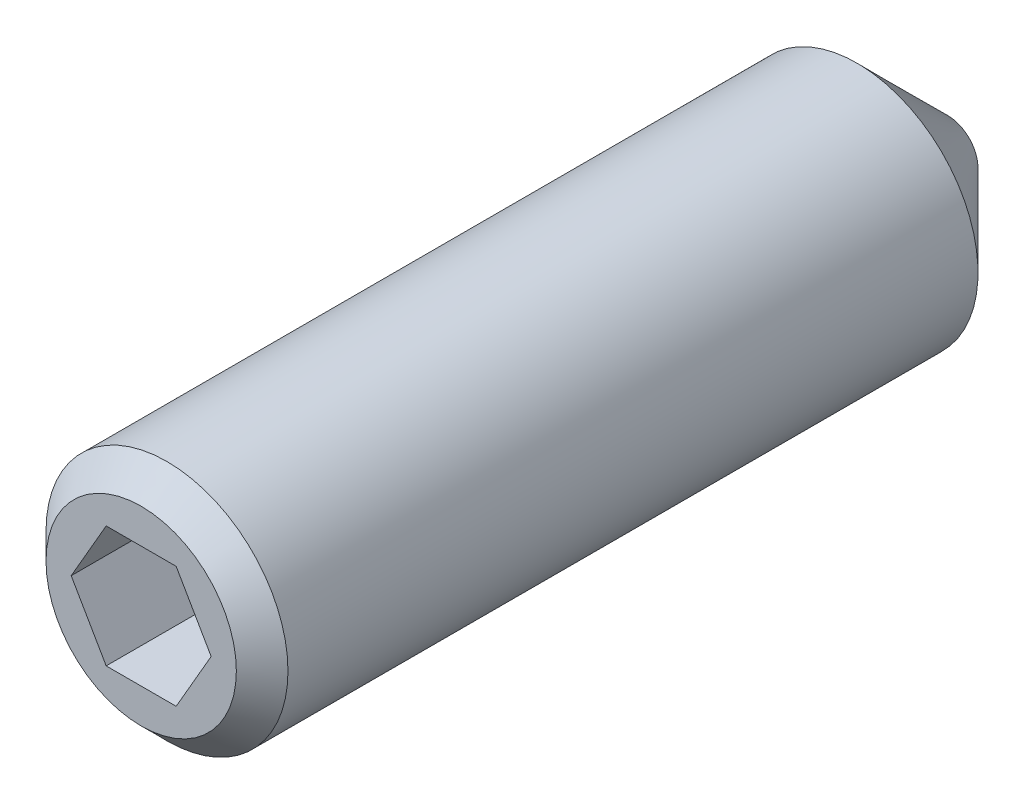
SolidWorks part; units mm, degrees
ref_plane "Front Plane" through (0, 0, 0) normal (0, 0, 1) x (1, 0, 0)
ref_plane "Top Plane" through (0, 0, 0) normal (0, 1, 0) x (1, 0, 0)
ref_plane "Right Plane" through (0, 0, 0) normal (1, 0, 0) x (0, 0, -1)
sketch "Sketch1" plane through (0, 0, 0) normal (0, 0, 1) x (1, 0, 0)
  circle A0 centre (0, 0) radius 1.5
  dimension "D1" = 3
extrude "Boss-Extrude1" add sketch "Sketch1" along normal blind 10 contours A0
sketch "Sketch2" plane through (0, 0, 10) normal (0, 0, 1) x (1, 0, 0)
  line L1 (0.8677, 0) -> (0.4338, 0.7514)
  line L2 (0.4338, 0.7514) -> (-0.4338, 0.7514)
  line L3 (-0.4338, 0.7514) -> (-0.8677, 0)
  line L4 (-0.8677, 0) -> (-0.4338, -0.7514)
  line L5 (-0.4338, -0.7514) -> (0.4338, -0.7514)
  line L6 (0.4338, -0.7514) -> (0.8677, 0)
  circle A0 centre (0, 0) radius 0.7514 construction
  dimension "D1" = 1.5028
extrude "Cut-Extrude1" cut sketch "Sketch2" against normal blind 1.2
sketch "Sketch3" plane through (0, 0, 10) normal (0, 0, 1) x (1, 0, 0)
  circle A0 centre (0, 0) radius 1.18
  dimension "D1" = 2.36
extrude "Cut-Extrude2" cut sketch "Sketch3" against normal blind 1.2 draft 45 flip side to cut
sketch "Sketch4" plane through (0, 0, 0) normal (0, 0, -1) x (-1, 0, 0)
  circle A0 centre (0, 0) radius 0.375
  dimension "D1" = 0.75
extrude "Cut-Extrude3" cut sketch "Sketch4" against normal blind 1.2 draft 45 flip side to cut
